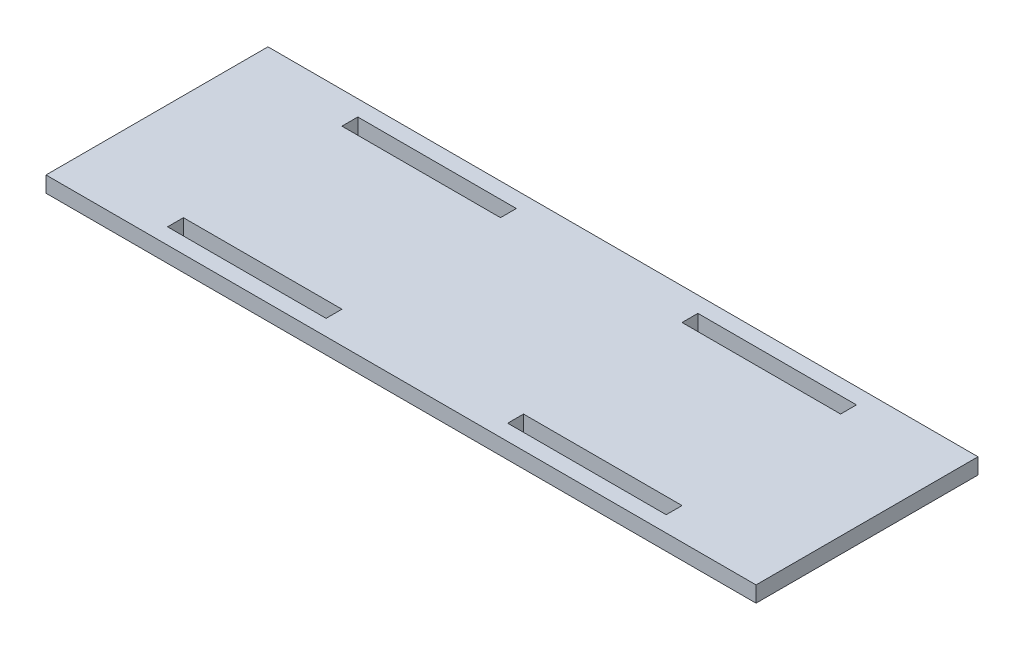
SolidWorks part; units mm, degrees
material "ABS"
ref_plane "Front Plane" through (0, 0, 0) normal (0, 0, 1) x (1, 0, 0)
ref_plane "Top Plane" through (0, 0, 0) normal (0, 1, 0) x (1, 0, 0)
ref_plane "Right Plane" through (0, 0, 0) normal (1, 0, 0) x (0, 0, -1)
sketch "Sketch1" plane through (0, 0, 0) normal (0, 1, 0) x (1, 0, 0)
  line L0 (0, 21) -> (134.36, 21) construction
  line L1 (0, 0) -> (134.36, 0)
  line L2 (0, 0) -> (0, 42)
  line L3 (0, 42) -> (134.36, 42)
  line L4 (134.36, 0) -> (134.36, 42)
  line L5 (20, 6) -> (50, 6)
  line L6 (20, 6) -> (20, 3)
  line L7 (20, 3) -> (50, 3)
  line L8 (50, 6) -> (50, 3)
  line L9 (84.36, 6) -> (114.36, 6)
  line L10 (84.36, 6) -> (84.36, 3)
  line L11 (84.36, 3) -> (114.36, 3)
  line L12 (114.36, 6) -> (114.36, 3)
  line L13 (114.36, 36) -> (114.36, 39)
  line L14 (84.36, 39) -> (114.36, 39)
  line L15 (84.36, 36) -> (84.36, 39)
  line L16 (84.36, 36) -> (114.36, 36)
  line L17 (50, 36) -> (50, 39)
  line L18 (20, 39) -> (50, 39)
  line L19 (20, 36) -> (20, 39)
  line L20 (20, 36) -> (50, 36)
  dimension "D1" = 134.36
  dimension "D2" = 42
  dimension "D3" = 30
  dimension "D4" = 3
  dimension "D5" = 3
  dimension "D6" = 30
  dimension "D7" = 3
  dimension "D8" = 20
  dimension "D9" = 20
  dimension "D10" = 3
extrude "Boss-Extrude1" add sketch "Sketch1" along normal blind 3
